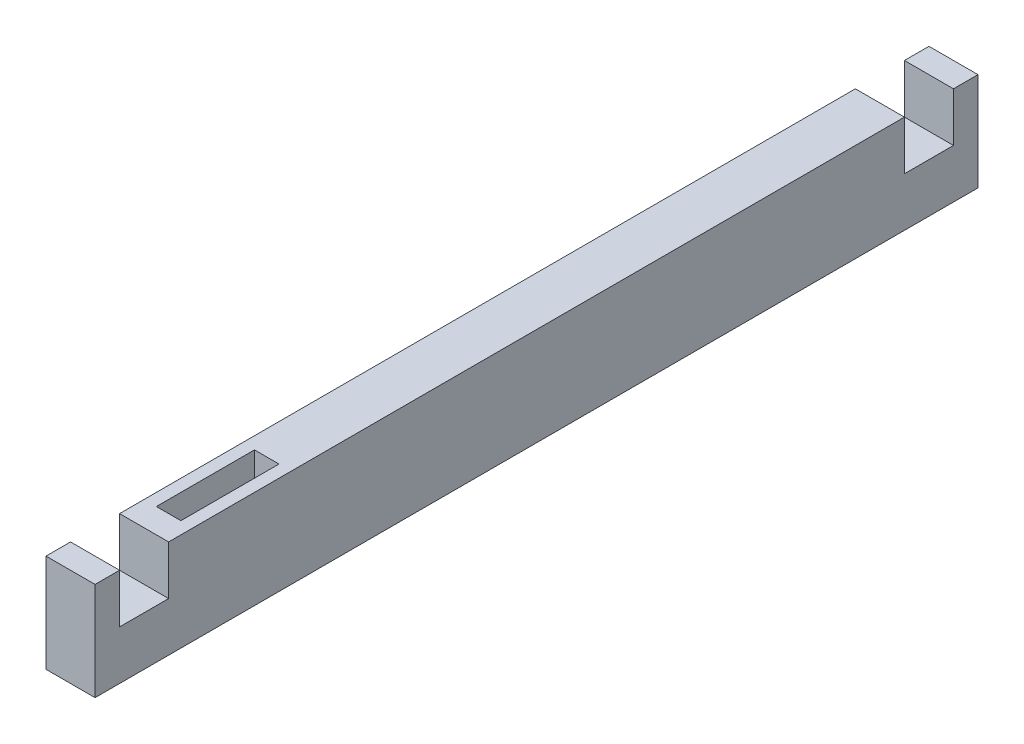
SolidWorks part; units mm, degrees
ref_plane "Front Plane" through (0, 0, 0) normal (0, 0, 1) x (1, 0, 0)
ref_plane "Top Plane" through (0, 0, 0) normal (0, 1, 0) x (1, 0, 0)
ref_plane "Right Plane" through (0, 0, 0) normal (1, 0, 0) x (0, 0, -1)
sketch "Sketch1" plane through (0, 0, 0) normal (0, 0, 1) x (1, 0, 0)
  line L1 (-25.4, -50.8) -> (25.4, -50.8)
  line L2 (-25.4, -50.8) -> (-25.4, 50.8)
  line L3 (-25.4, 50.8) -> (25.4, 50.8)
  line L4 (25.4, -50.8) -> (25.4, 50.8)
  line L5 (-25.4, -50.8) -> (25.4, 50.8) construction
  line L6 (-25.4, 50.8) -> (25.4, -50.8) construction
  point P0 (0, 0)
  dimension "D1" = 101.6
  dimension "D2" = 50.8
extrude "Boss-Extrude1" add sketch "Sketch1" along normal blind 914.4
sketch "Sketch2" plane through (25.4, 0, 0) normal (1, 0, 0) x (0, 0, -1)
  line L0 (-914.4, 50.8) -> (0, 50.8) construction
  line L1 (279.4, 50.8) -> (279.4, 0)
  line L2 (-889, 50.8) -> (-838.2, 50.8)
  line L3 (-889, 50.8) -> (-889, 0)
  line L4 (-889, 0) -> (-838.2, 0)
  line L5 (-838.2, 50.8) -> (-838.2, 0)
  line L6 (279.4, 50.8) -> (330.2, 50.8)
  line L7 (330.2, 50.8) -> (330.2, 0)
  line L8 (279.4, 0) -> (330.2, 0)
  line L9 (1447.8, 50.8) -> (1447.8, 0)
  line L10 (1447.8, 50.8) -> (1498.6, 50.8)
  line L11 (1498.6, 50.8) -> (1498.6, 0)
  line L12 (1447.8, 0) -> (1498.6, 0)
  dimension "D1" = 25.4
  dimension "D2" = 50.8
  dimension "D3" = 50.8
  dimension "D4" = 3
extrude "Cut-Extrude1" cut sketch "Sketch2" against normal through all both and the other way through all
ref_plane "Plane1" through (0, 0, 457.2) normal (0, 0, 1) x (1, 0, 0)
mirror "Mirror1" about plane through (0, 0, 457.2) normal (0, 0, 1) of "Cut-Extrude1"
sketch "Sketch3" plane through (0, -50.8, 0) normal (0, -1, 0) x (-1, 0, 0)
  line L0 (0, -914.4) -> (0, -762) construction
  line L1 (25.4, -914.4) -> (-25.4, -914.4) construction
  line L3 (12.7, -812.8) -> (-12.7, -812.8)
  line L4 (12.7, -812.8) -> (12.7, -711.2)
  line L5 (12.7, -711.2) -> (-12.7, -711.2)
  line L6 (-12.7, -812.8) -> (-12.7, -711.2)
  line L7 (12.7, -812.8) -> (-12.7, -711.2) construction
  line L8 (12.7, -711.2) -> (-12.7, -812.8) construction
  dimension "D1" = 152.4
  dimension "D2" = 101.6
  dimension "D3" = 25.4
extrude "Cut-Extrude2" cut sketch "Sketch3" against normal through all
